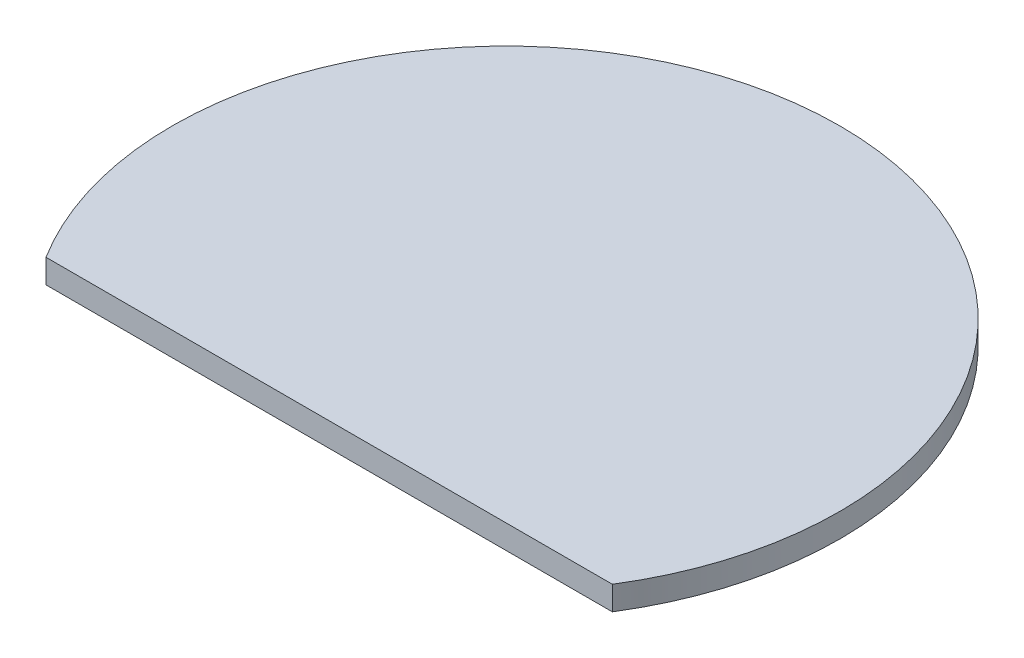
SolidWorks part; units mm, degrees
ref_plane "Front Plane" through (0, 0, 0) normal (0, 0, 1) x (1, 0, 0)
ref_plane "Top Plane" through (0, 0, 0) normal (0, 1, 0) x (1, 0, 0)
ref_plane "Right Plane" through (0, 0, 0) normal (1, 0, 0) x (0, 0, -1)
sketch "Sketch1" plane through (0, 0, 0) normal (0, 1, 0) x (1, 0, 0)
  line L0 (-11.84, -7.3957) -> (11.84, -7.3957)
  arc A0 (11.84, -7.3957) -> (-11.84, -7.3957) centre (0, 0) ccw
  dimension "D1" = 27.92
  dimension "D2" = 23.68
extrude "Boss-Extrude1" add sketch "Sketch1" along normal blind 1
